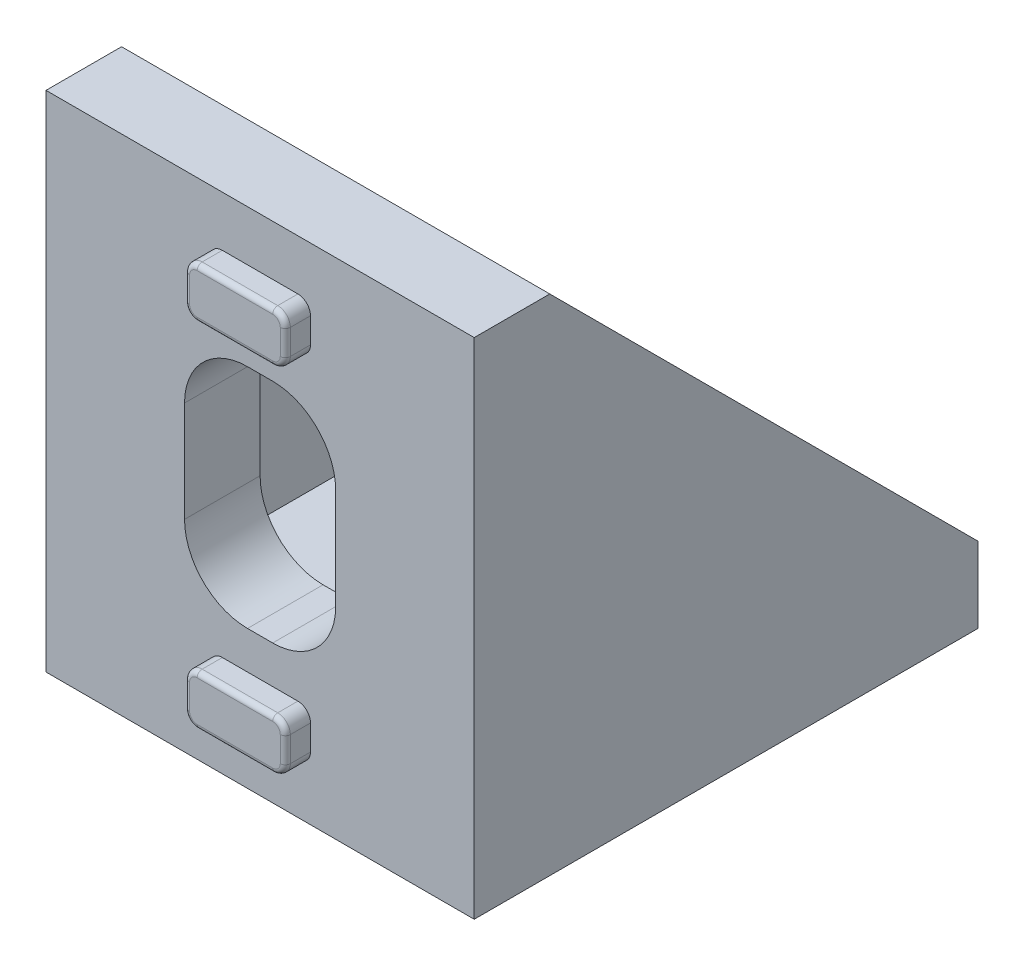
SolidWorks part; units mm, degrees
ref_plane "Front Plane" through (0, 0, 0) normal (0, 0, 1) x (1, 0, 0)
ref_plane "Top Plane" through (0, 0, 0) normal (0, 1, 0) x (1, 0, 0)
ref_plane "Right Plane" through (0, 0, 0) normal (1, 0, 0) x (0, 0, -1)
sketch "Sketch1" plane through (0, 0, 0) normal (0, 1, 0) x (1, 0, 0)
  line L1 (-8.5, -10) -> (8.5, -10)
  line L2 (-8.5, -10) -> (-8.5, 10)
  line L3 (-8.5, 10) -> (8.5, 10)
  line L4 (8.5, -10) -> (8.5, 10)
  line L5 (-8.5, -10) -> (8.5, 10) construction
  line L6 (-8.5, 10) -> (8.5, -10) construction
  point P0 (0, 0)
  dimension "D1" = 20
  dimension "D2" = 17
extrude "Boss-Extrude1" add sketch "Sketch1" along normal blind 3
sketch "Sketch2" plane through (0, 3, 0) normal (0, 1, 0) x (1, 0, 0)
  line L0 (8.5, -10) -> (8.5, 10) construction
  line L1 (-8.5, -10) -> (8.5, -10)
  line L2 (-8.5, -10) -> (-8.5, -7)
  line L3 (-8.5, -7) -> (8.5, -7)
  line L4 (8.5, -10) -> (8.5, -7)
  dimension "D1" = 3
extrude "Boss-Extrude2" add sketch "Sketch2" along normal blind 17
sketch "Sketch3" plane through (8.5, 0, 0) normal (1, 0, 0) x (0, 0, -1)
  line L0 (-7, 20) -> (10, 3)
sketch "Sketch4" plane through (-8.5, 0, 0) normal (-1, 0, 0) x (0, 0, 1)
  line L0 (7, 20) -> (-10, 3)
rib "Rib1" sketch "Sketch3" sketch "Sketch3" thickness 2 extrusion direction parallel to sketch draft on no parameters "D1"=2
rib "Rib4" sketch "Sketch4" sketch "Sketch4" thickness 2 extrusion direction parallel to sketch draft on no parameters "D1"=2
sketch "Sketch5" plane through (0, 0, 10) normal (0, 0, 1) x (1, 0, 0)
  line L0 (0, 20) -> (0, 0) construction
  line L1 (-8.5, 20) -> (8.5, 20) construction
  line L2 (-8.5, 0) -> (8.5, 0) construction
  line L4 (-0.5, 5.5) -> (0.5, 5.5)
  line L5 (-3, 8) -> (-3, 12)
  line L6 (-0.5, 14.5) -> (0.5, 14.5)
  line L7 (3, 8) -> (3, 12)
  line L8 (-3, 5.5) -> (3, 14.5) construction
  line L9 (-3, 14.5) -> (3, 5.5) construction
  arc A0 (-3, 8) -> (-0.5, 5.5) centre (-0.5, 8) ccw
  arc A1 (3, 8) -> (0.5, 5.5) centre (0.5, 8) cw
  arc A2 (3, 12) -> (0.5, 14.5) centre (0.5, 12) ccw
  arc A3 (-0.5, 14.5) -> (-3, 12) centre (-0.5, 12) ccw
  point P6 (0, 10)
  dimension "D3" = 2.5
  dimension "D1" = 9
  dimension "D2" = 6
extrude "Cut-Extrude1" cut sketch "Sketch5" against normal blind 17
sketch "Sketch6" plane through (0, 0, 0) normal (0, -1, 0) x (1, 0, 0)
  line L0 (0, 10) -> (0, -10) construction
  line L1 (-8.5, 10) -> (8.5, 10) construction
  line L2 (8.5, -10) -> (-8.5, -10) construction
  line L4 (-0.5, 4.5) -> (0.5, 4.5)
  line L5 (-3, 2) -> (-3, -2)
  line L6 (-0.5, -4.5) -> (0.5, -4.5)
  line L7 (3, 2) -> (3, -2)
  line L8 (-3, 4.5) -> (3, -4.5) construction
  line L9 (-3, -4.5) -> (3, 4.5) construction
  arc A0 (-3, -2) -> (-0.5, -4.5) centre (-0.5, -2) ccw
  arc A1 (0.5, -4.5) -> (3, -2) centre (0.5, -2) ccw
  arc A2 (3, 2) -> (0.5, 4.5) centre (0.5, 2) ccw
  arc A3 (-0.5, 4.5) -> (-3, 2) centre (-0.5, 2) ccw
  point P6 (0, 0)
  dimension "D3" = 2.5
  dimension "D1" = 9
  dimension "D2" = 6
extrude "Cut-Extrude2" cut sketch "Sketch6" against normal blind 17
sketch "Sketch7" plane through (0, 0, 0) normal (0, -1, 0) x (1, 0, 0)
  line L0 (0, 10) -> (0, 7) construction
  line L1 (-8.5, 10) -> (8.5, 10) construction
  line L2 (8.5, 0) -> (-8.5, 0) construction
  line L3 (1.5, 8) -> (-1.5, 8)
  line L4 (2, 7.5) -> (2, 6.5)
  line L5 (1.5, 6) -> (-1.5, 6)
  line L6 (-2, 7.5) -> (-2, 6.5)
  line L7 (2, 8) -> (-2, 6) construction
  line L8 (2, 6) -> (-2, 8) construction
  line L9 (8.5, 10) -> (8.5, -10) construction
  line L10 (-8.5, -10) -> (-8.5, 10) construction
  line L11 (2, -6) -> (-2, -8) construction
  line L12 (2, -8) -> (-2, -6) construction
  line L13 (0, -10) -> (0, -7) construction
  line L14 (-2, -7.5) -> (-2, -6.5)
  line L15 (1.5, -6) -> (-1.5, -6)
  line L16 (2, -7.5) -> (2, -6.5)
  line L17 (1.5, -8) -> (-1.5, -8)
  arc A0 (-1.5, 8) -> (-2, 7.5) centre (-1.5, 7.5) ccw
  arc A1 (-1.5, 6) -> (-2, 6.5) centre (-1.5, 6.5) cw
  arc A2 (1.5, 6) -> (2, 6.5) centre (1.5, 6.5) ccw
  arc A3 (1.5, 8) -> (2, 7.5) centre (1.5, 7.5) cw
  arc A4 (1.5, -8) -> (2, -7.5) centre (1.5, -7.5) ccw
  arc A5 (1.5, -6) -> (2, -6.5) centre (1.5, -6.5) cw
  arc A6 (-1.5, -6) -> (-2, -6.5) centre (-1.5, -6.5) ccw
  arc A7 (-1.5, -8) -> (-2, -7.5) centre (-1.5, -7.5) cw
  dimension "D4" = 0.5
  dimension "D1" = 3
  dimension "D2" = 2
  dimension "D3" = 4
extrude "Boss-Extrude3" add sketch "Sketch7" along normal blind 1
sketch "Sketch8" plane through (0, 0, 10) normal (0, 0, 1) x (1, 0, 0)
  line L0 (0, 0) -> (0, 3) construction
  line L2 (8.5, 10) -> (-8.5, 10) construction
  line L3 (-1.5, 4) -> (1.5, 4)
  line L4 (-2, 3.5) -> (-2, 2.5)
  line L5 (-1.5, 2) -> (1.5, 2)
  line L6 (2, 3.5) -> (2, 2.5)
  line L7 (-2, 4) -> (2, 2) construction
  line L8 (-2, 2) -> (2, 4) construction
  line L9 (8.5, 20) -> (8.5, 0) construction
  line L10 (-8.5, 20) -> (-8.5, 0) construction
  line L11 (-2, 18) -> (2, 16) construction
  line L12 (-2, 16) -> (2, 18) construction
  line L13 (0, 20) -> (0, 17) construction
  line L14 (2, 16.5) -> (2, 17.5)
  line L15 (-1.5, 18) -> (1.5, 18)
  line L16 (-2, 16.5) -> (-2, 17.5)
  line L17 (-1.5, 16) -> (1.5, 16)
  arc A0 (-1.5, 4) -> (-2, 3.5) centre (-1.5, 3.5) ccw
  arc A1 (-2, 2.5) -> (-1.5, 2) centre (-1.5, 2.5) ccw
  arc A2 (1.5, 2) -> (2, 2.5) centre (1.5, 2.5) ccw
  arc A3 (1.5, 4) -> (2, 3.5) centre (1.5, 3.5) cw
  arc A4 (1.5, 16) -> (2, 16.5) centre (1.5, 16.5) ccw
  arc A5 (1.5, 18) -> (2, 17.5) centre (1.5, 17.5) cw
  arc A6 (-2, 17.5) -> (-1.5, 18) centre (-1.5, 17.5) cw
  arc A7 (-1.5, 16) -> (-2, 16.5) centre (-1.5, 16.5) cw
  dimension "D4" = 0.5
  dimension "D1" = 3
  dimension "D2" = 2
  dimension "D3" = 4
extrude "Boss-Extrude4" add sketch "Sketch8" along normal blind 1
fillet "Fillet1" radius 0.2 32 edges at (0, -1, -8) (-1.8536, -1, -7.8536) (-2, -1, -7) (-1.8536, -1, -6.1464) (0, -1, -6) (1.8536, -1, -6.1464) (2, -1, -7) (1.8536, -1, -7.8536) (0, -1, 8) (1.8536, -1, 7.8536) (2, -1, 7) (1.8536, -1, 6.1464) (0, -1, 6) (-1.8536, -1, 6.1464) (-2, -1, 7) (-1.8536, -1, 7.8536) (0, 16, 11) (-1.8536, 16.1464, 11) (-2, 17, 11) (-1.8536, 17.8536, 11) (0, 18, 11) (1.8536, 17.8536, 11) (2, 17, 11) (1.8536, 16.1464, 11) (0, 4, 11) (1.8536, 3.8536, 11) (2, 3, 11) (1.8536, 2.1464, 11) (0, 2, 11) (-1.8536, 2.1464, 11) (-2, 3, 11) (-1.8536, 3.8536, 11)
